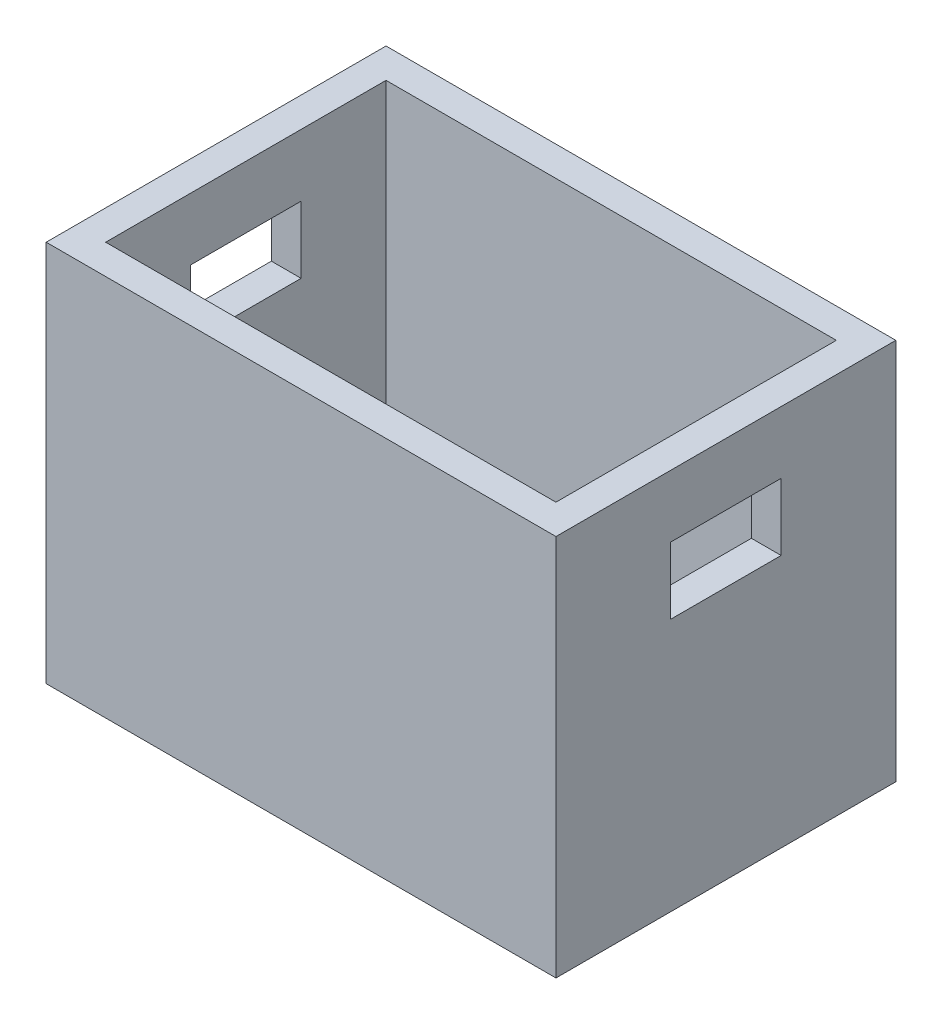
SolidWorks part; units mm, degrees
ref_plane "Front Plane" through (0, 0, 0) normal (0, 0, 1) x (1, 0, 0)
ref_plane "Top Plane" through (0, 0, 0) normal (0, 1, 0) x (1, 0, 0)
ref_plane "Right Plane" through (0, 0, 0) normal (1, 0, 0) x (0, 0, -1)
sketch "Sketch1" plane through (0, 0, 0) normal (0, 1, 0) x (1, 0, 0)
  line L1 (-30, -20) -> (30, -20)
  line L2 (-30, -20) -> (-30, 20)
  line L3 (-30, 20) -> (30, 20)
  line L4 (30, -20) -> (30, 20)
  line L5 (-30, -20) -> (30, 20) construction
  line L6 (-30, 20) -> (30, -20) construction
  point P0 (0, 0)
  dimension "D1" = 60
  dimension "D2" = 40
extrude "Boss-Extrude1" add sketch "Sketch1" along normal blind 45
shell "Shell1" thickness 3.5
sketch "Sketch2" plane through (30, 0, 0) normal (1, 0, 0) x (0, 0, -1)
  line L0 (0, 45) -> (0, 0) construction
  line L1 (-20, 45) -> (20, 45) construction
  line L2 (0, 22.5) -> (20, 45) construction
  line L3 (-20, 45) -> (0, 22.5) construction
  line L4 (20, 22.5) -> (0, 45) construction
  line L5 (20, 45) -> (20, 0) construction
  line L6 (0, 45) -> (-20, 22.5) construction
  line L7 (-20, 45) -> (-20, 0) construction
  line L8 (-20, 33.75) -> (20, 33.75) construction
  line L10 (-6.5039, 37.6831) -> (6.5039, 37.6831)
  line L11 (-6.5039, 37.6831) -> (-6.5039, 29.8169)
  line L12 (-6.5039, 29.8169) -> (6.5039, 29.8169)
  line L13 (6.5039, 37.6831) -> (6.5039, 29.8169)
  line L14 (-6.5039, 37.6831) -> (6.5039, 29.8169) construction
  line L15 (-6.5039, 29.8169) -> (6.5039, 37.6831) construction
  point P18 (0, 33.75)
extrude "Cut-Extrude1" cut sketch "Sketch2" against normal through all
